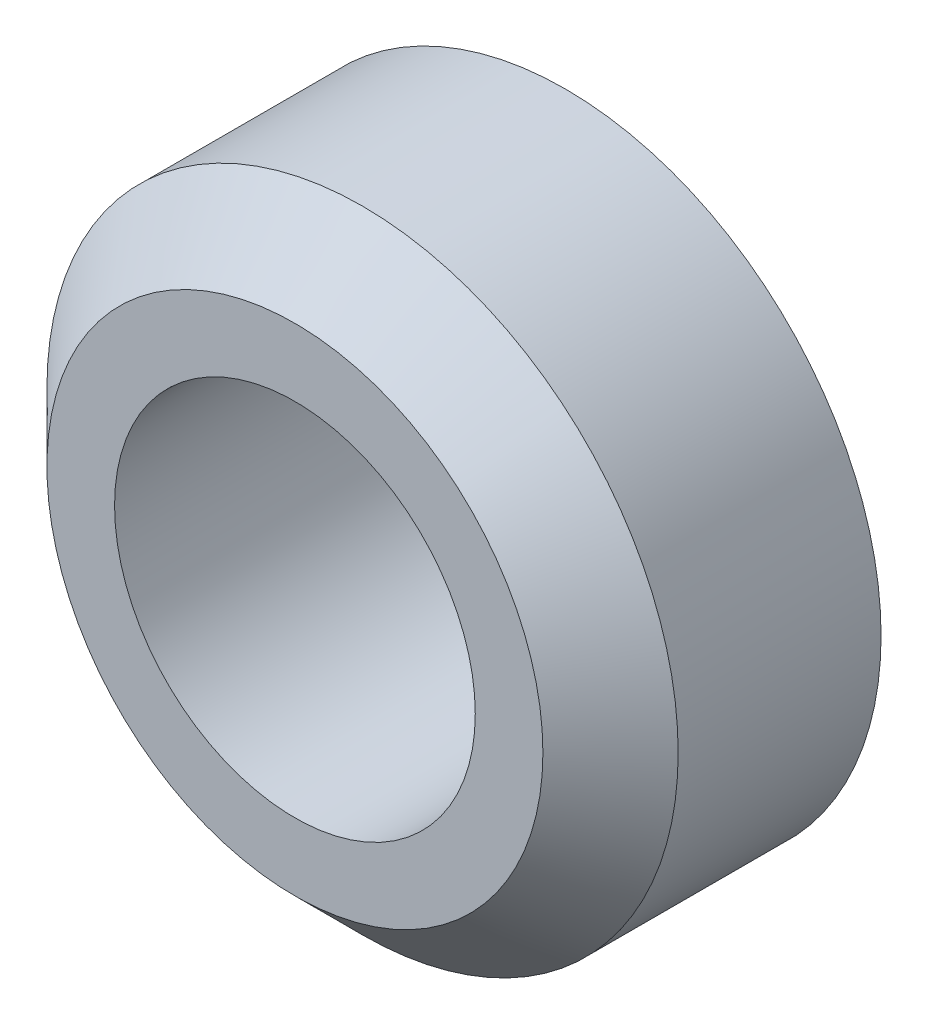
SolidWorks part; units mm, degrees
material "PEI"
ref_plane "Piano frontale" through (0, 0, 0) normal (0, 0, 1) x (1, 0, 0)
ref_plane "Piano superiore" through (0, 0, 0) normal (0, 1, 0) x (1, 0, 0)
ref_plane "Piano destro" through (0, 0, 0) normal (1, 0, 0) x (0, 0, -1)
sketch "Schizzo1" plane through (0, 0, 0) normal (0, 0, 1) x (1, 0, 0)
  circle A0 centre (0, 0) radius 4
  circle A1 centre (0, 0) radius 7
  dimension "D1" = 8
  dimension "D2" = 14
extrude "Estrusione-Estrusione1" add sketch "Schizzo1" along normal blind 6
chamfer "Smusso1" distance 1.5 angle 45 1 edges at (7, 0, 6)
